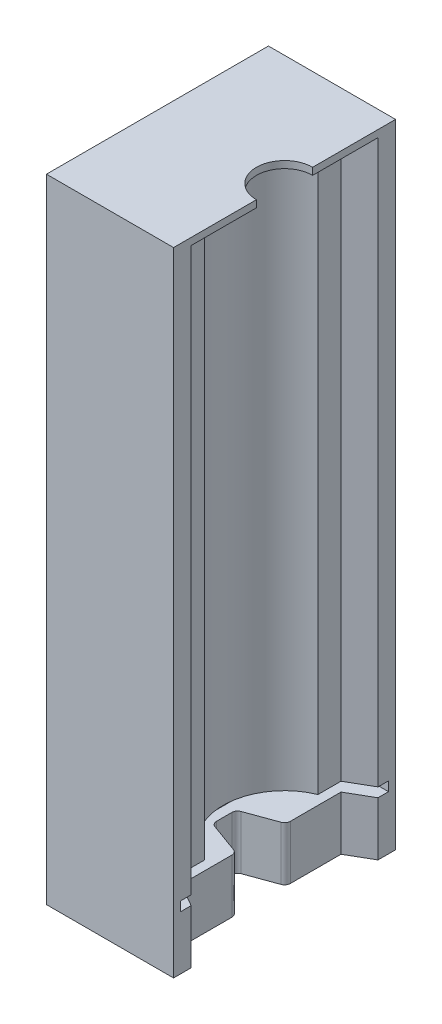
SolidWorks part; units mm, degrees
ref_plane "Спереди" through (0, 0, 0) normal (0, 0, 1) x (1, 0, 0)
ref_plane "Сверху" through (0, 0, 0) normal (0, 1, 0) x (1, 0, 0)
ref_plane "Справа" through (0, 0, 0) normal (1, 0, 0) x (0, 0, -1)
sketch "Эскиз1" plane through (0, 0, 0) normal (0, 1, 0) x (1, 0, 0)
  line L0 (0, -15.95) -> (0, -18.95)
  line L1 (12, -17.75) -> (-12, -17.75) construction
  line L2 (12, -17.75) -> (12, 17.75) construction
  line L3 (12, 17.75) -> (-12, 17.75) construction
  line L4 (-12, -17.75) -> (-12, 17.75) construction
  line L5 (12, -17.75) -> (-12, 17.75) construction
  line L6 (12, 17.75) -> (-12, -17.75) construction
  line L7 (0, 18.95) -> (-21.7, 18.95)
  line L8 (0, 18.95) -> (0, 15.95)
  line L9 (0, -18.95) -> (-21.7, -18.95)
  line L10 (-21.7, 18.95) -> (-21.7, -18.95)
  line L11 (-4, 9.7082) -> (-4, 13.6406)
  line L12 (-4, 13.6406) -> (0, 15.95)
  line L13 (0, 0) -> (-43.4608, 0) construction
  line L14 (0, -18.95) -> (0, -15.95)
  line L15 (-4, -13.6406) -> (0, -15.95)
  line L16 (-4, -9.7082) -> (-4, -13.6406)
  line L17 (-11.7, 17.75) -> (-11.7, -17.75)
  line L18 (-21.7, 17.75) -> (-11.7, 17.75)
  line L19 (-21.7, -17.75) -> (-11.7, -17.75)
  circle A0 centre (0, 0) radius 10.5 construction
  arc A1 (-4, 9.7082) -> (-4, -9.7082) centre (0, 0) ccw
  point P12 (-10.5, 0)
  point P15 (-4, 11.6744)
  dimension "D1" = 21
  dimension "D6" = 4
  dimension "D2" = 35.5
  dimension "D3" = 24
  dimension "D4" = 1.2
  dimension "D5" = 1.2
  dimension "D7" = 3.9324
  dimension "D8" = 3
  dimension "D9" = 120
  dimension "D10" = 10
extrude "Бобышка-Вытянуть1" add sketch "Эскиз1" along normal blind 96 contours A1 L11 L12 L8 L7 L10 L18 L17 L19 L9 L0 L15 L16
sketch "Эскиз2" plane through (0, 96, 0) normal (0, 1, 0) x (1, 0, 0)
  line L0 (0, -4.8) -> (0, -18.95)
  line L1 (-21.7, 18.95) -> (0, 18.95)
  line L2 (-21.7, 18.95) -> (-21.7, -18.95)
  line L3 (-21.7, -18.95) -> (0, -18.95)
  line L4 (0, 18.95) -> (0, 4.8)
  arc A0 (0, 4.8) -> (0, -4.8) centre (0, 0) ccw
  dimension "D1" = 9.6
  dimension "D2" = 18.95
extrude "Бобышка-Вытянуть2" add sketch "Эскиз2" along normal blind 1.2
sketch "Эскиз3" plane through (0, 0, 0) normal (0, -1, 0) x (1, 0, 0)
  line L0 (0, -18.95) -> (0, -17.75)
  line L1 (12, -17.75) -> (-12, -17.75) construction
  line L2 (12, -17.75) -> (12, 17.75) construction
  line L3 (12, 17.75) -> (-12, 17.75) construction
  line L4 (-12, -17.75) -> (-12, 17.75) construction
  line L5 (12, -17.75) -> (-12, 17.75) construction
  line L6 (12, 17.75) -> (-12, -17.75) construction
  line L7 (0, -17.75) -> (-7, -17.75)
  line L8 (-7, -17.75) -> (-12, -9.0897)
  line L9 (-12, -9.0897) -> (-12, 9.0897)
  line L10 (-12, 9.0897) -> (-7, 17.75)
  line L11 (-7, 17.75) -> (0, 17.75)
  line L12 (0, 17.75) -> (0, 18.95)
  line L13 (0, 18.95) -> (-21.7, 18.95)
  line L14 (-21.7, 18.95) -> (-21.7, -18.95)
  line L15 (-21.7, -18.95) -> (0, -18.95)
  line L16 (-11.7, -17.75) -> (-11.7, 17.75) construction
  circle A0 centre (-17.7, 2.45) radius 1.6
  circle A1 centre (-17.7, -2.05) radius 0.6
  circle A2 centre (-17.7, 6.95) radius 0.6
  point P0 (0, 0)
  point P26 (0, 0)
  point P29 (0, 0)
  dimension "D7" = 3.2
  dimension "D8" = 1.2
  dimension "D9" = 1.2
  dimension "D1" = 7
  dimension "D2" = 30
  dimension "D3" = 30
  dimension "D4" = 7
  dimension "D5" = 18.1795
  dimension "D6" = 1.2
  dimension "D10" = 4.5
  dimension "D11" = 4.5
  dimension "D12" = 6
  dimension "D13" = 21.4
extrude "Бобышка-Вытянуть3" add sketch "Эскиз3" along normal blind 1.6
sketch "Эскиз4" plane through (0, -1.6, 0) normal (0, -1, 0) x (1, 0, 0)
  line L0 (0, -17.75) -> (0, -18.95)
  line L1 (0, -18.95) -> (-21.7, -18.95)
  line L2 (-21.7, -18.95) -> (-21.7, 18.95)
  line L3 (-21.7, 18.95) -> (0, 18.95)
  line L4 (0, 18.95) -> (0, 17.75)
  line L5 (-4, 9.7082) -> (-4, 4.2958)
  line L6 (-4, 4.2958) -> (-10.3078, 2)
  line L7 (-10.3078, 2) -> (-10.3078, -2)
  line L8 (-4, -9.7082) -> (-4, -4.2958)
  line L9 (-4, -4.2958) -> (-10.3078, -2)
  line L11 (0, 17.75) -> (-7, 17.75)
  line L12 (-7, 17.75) -> (-11.7, 9.6094)
  line L13 (-11.7, 9.6094) -> (-11.7, -9.6094)
  line L14 (-11.7, -9.6094) -> (-7, -17.75)
  line L15 (-7, -17.75) -> (0, -17.75)
  line L16 (0, -17.75) -> (0, -15.95)
  line L17 (0, -15.95) -> (-4, -13.6406)
  line L18 (-4, -13.6406) -> (-4, -9.7082)
  line L19 (-4, 9.7082) -> (-4, 13.6406)
  line L20 (-4, 13.6406) -> (0, 15.95)
  line L21 (0, 15.95) -> (0, 17.75)
  line L27 (0, -17.75) -> (0, -15.95)
  line L28 (0, -15.95) -> (-4, -13.6406)
  line L29 (-4, -13.6406) -> (-4, -9.7082)
  line L30 (-4, 9.7082) -> (-4, 13.6406)
  line L31 (-4, 13.6406) -> (0, 15.95)
  line L32 (0, 15.95) -> (0, 17.75)
  circle A0 centre (-17.7, 6.95) radius 0.6 construction
  arc A1 (-4, 9.7082) -> (-4, -9.7082) centre (0, 0) ccw
  circle A3 centre (-17.7, 2.45) radius 1.6 construction
  circle A4 centre (-17.7, -2.05) radius 0.6 construction
  circle A5 centre (-17.7, 6.95) radius 0.6
  circle A6 centre (-17.7, 2.45) radius 1.6
  circle A7 centre (-17.7, -2.05) radius 0.6
  circle A8 centre (-13.2, 10.45) radius 7.5 construction
  circle A9 centre (-17.7, 2.6558) radius 1.5 construction
  dimension "D2" = 15
  dimension "D3" = 8.5
  dimension "D4" = 8.5
  dimension "D5" = 110
  dimension "D6" = 110
  dimension "D7" = 9
  dimension "D8" = 4
  dimension "D1" = 0
extrude "Бобышка-Вытянуть4" add sketch "Эскиз4" along normal blind 1.2
fillet "Скругление1" radius 1 4 edges at (-10.3078, -2.2, -2) (-10.3078, -2.2, 2) (-4, -2.2, 4.2958) (-4, -2.2, -4.2958)
sketch "Эскиз5" plane through (0, -2.8, 0) normal (0, -1, 0) x (1, 0, 0)
  line L0 (-21.7, 18.95) -> (-21.7, -18.95) construction
  line L1 (0, 18.95) -> (-21.7, 18.95) construction
  circle A0 centre (-13.2, 10.25) radius 1.5
  dimension "D1" = 3
  dimension "D2" = 8.5
  dimension "D3" = 8.7
extrude "Вырез-Вытянуть1" cut sketch "Эскиз5" against normal blind 2
sketch "Эскиз6" plane through (0, -2.8, 0) normal (0, -1, 0) x (1, 0, 0)
  line L0 (-10.3078, 0) -> (-30.784, 0) construction
  line L1 (-10.3078, -1.2998) -> (-10.3078, 1.2998) construction
  circle A0 centre (-13.2, 10.25) radius 1.5 construction
  circle A1 centre (-13.2, 10.25) radius 1.5 construction
  circle A2 centre (-13.2, -10.25) radius 1.5
extrude "Вырез-Вытянуть2" cut sketch "Эскиз6" against normal blind 2
sketch "Эскиз9" plane through (0, -2.8, 0) normal (0, -1, 0) x (1, 0, 0)
  line L0 (-1.2, 16.6428) -> (-1.2, 17.75)
  line L1 (-1.2, 17.75) -> (-20.5, 17.75)
  line L2 (-20.5, 17.75) -> (-20.5, -17.75)
  line L3 (-20.5, -17.75) -> (-1.2, -17.75)
  line L4 (-1.2, -17.75) -> (-1.2, -16.6428)
  line L5 (-1.2, -16.6428) -> (-5.2, -14.3334)
  line L6 (-5.2, -14.3334) -> (-5.2, -5.1361)
  line L7 (-5.2, -5.1361) -> (-10.0602, -3.3671)
  line L8 (-11.5078, -1.2998) -> (-11.5078, 1.2998)
  line L9 (-10.0602, 3.3671) -> (-5.2, 5.1361)
  line L10 (-5.2, 5.1361) -> (-5.2, 14.3334)
  line L11 (-5.2, 14.3334) -> (-1.2, 16.6428)
  line L12 (-9.6498, 2.2395) -> (-4.658, 4.0564)
  line L13 (-4, 4.996) -> (-4, 13.6406)
  line L14 (-4, 13.6406) -> (0, 15.95)
  line L15 (0, 15.95) -> (0, 18.95)
  line L16 (0, 18.95) -> (-21.7, 18.95)
  line L17 (-21.7, 18.95) -> (-21.7, -18.95)
  line L18 (-21.7, -18.95) -> (0, -18.95)
  line L19 (0, -18.95) -> (0, -15.95)
  line L20 (0, -15.95) -> (-4, -13.6406)
  line L21 (-4, -13.6406) -> (-4, -4.996)
  line L22 (-4.658, -4.0564) -> (-9.6498, -2.2395)
  line L23 (-10.3078, -1.2998) -> (-10.3078, 1.2998)
  line L24 (-9.6498, 2.2395) -> (-4.658, 4.0564)
  line L25 (-4, 4.996) -> (-4, 13.6406)
  line L26 (-4, 13.6406) -> (0, 15.95)
  line L27 (0, 15.95) -> (0, 18.95)
  line L28 (0, 18.95) -> (-21.7, 18.95)
  line L29 (-21.7, 18.95) -> (-21.7, -18.95)
  line L30 (-21.7, -18.95) -> (0, -18.95)
  line L31 (0, -18.95) -> (0, -15.95)
  line L32 (0, -15.95) -> (-4, -13.6406)
  line L33 (-4, -13.6406) -> (-4, -4.996)
  line L34 (-4.658, -4.0564) -> (-9.6498, -2.2395)
  line L35 (-10.3078, -1.2998) -> (-10.3078, 1.2998)
  arc A0 (-5.2, -5.1361) -> (-5.2, -5.1361) centre (-5.2, -5.1361) ccw
  arc A1 (-11.5078, -1.2998) -> (-10.0602, -3.3671) centre (-9.3078, -1.2998) ccw
  arc A2 (-10.0602, 3.3671) -> (-11.5078, 1.2998) centre (-9.3078, 1.2998) ccw
  arc A3 (-5.2, 5.1361) -> (-5.2, 5.1361) centre (-5.2, 5.1361) ccw
  arc A4 (-4.658, 4.0564) -> (-4, 4.996) centre (-5, 4.996) ccw
  arc A5 (-4, -4.996) -> (-4.658, -4.0564) centre (-5, -4.996) ccw
  arc A6 (-10.3078, -1.2998) -> (-9.6498, -2.2395) centre (-9.3078, -1.2998) ccw
  arc A7 (-9.6498, 2.2395) -> (-10.3078, 1.2998) centre (-9.3078, 1.2998) ccw
  arc A8 (-4.658, 4.0564) -> (-4, 4.996) centre (-5, 4.996) ccw
  arc A9 (-4, -4.996) -> (-4.658, -4.0564) centre (-5, -4.996) ccw
  arc A10 (-10.3078, -1.2998) -> (-9.6498, -2.2395) centre (-9.3078, -1.2998) ccw
  arc A11 (-9.6498, 2.2395) -> (-10.3078, 1.2998) centre (-9.3078, 1.2998) ccw
  dimension "D1" = 0
  dimension "D2" = 1.2
extrude "Бобышка-Вытянуть6" add sketch "Эскиз9" along normal blind 8
sketch "Эскиз10" plane through (0, -10.8, 0) normal (0, -1, 0) x (1, 0, 0)
  line L0 (-1.2, 17.75) -> (-1.2, 16.6428)
  line L1 (-1.2, 16.6428) -> (-5.2, 14.3334)
  line L2 (-5.2, 14.3334) -> (-5.2, 17.75)
  line L3 (-1.2, 17.75) -> (-20.5, 17.75) construction
  line L4 (-5.2, 17.75) -> (-1.2, 17.75)
  line L5 (-16.5, 17.75) -> (-20.5, 13.75)
  line L6 (-20.5, 17.75) -> (-20.5, -17.75) construction
  line L7 (-20.5, 13.75) -> (-20.5, 17.75)
  line L8 (-20.5, 17.75) -> (-16.5, 17.75)
  line L9 (-10.3078, 0) -> (-20.5, 0) construction
  line L10 (-10.3078, -1.2998) -> (-10.3078, 1.2998) construction
  line L11 (-20.5, -13.75) -> (-20.5, -17.75)
  line L12 (-16.5, -17.75) -> (-20.5, -13.75)
  line L13 (-20.5, -17.75) -> (-16.5, -17.75)
  line L14 (-5.2, -14.3334) -> (-5.2, -17.75)
  line L15 (-1.2, -16.6428) -> (-5.2, -14.3334)
  line L16 (-1.2, -17.75) -> (-1.2, -16.6428)
  line L17 (-5.2, -17.75) -> (-1.2, -17.75)
  circle A0 centre (-3.6, 16.55) radius 0.6
  circle A1 centre (-19.3, 16.55) radius 0.6
  circle A2 centre (-19.3, -16.55) radius 0.6
  circle A3 centre (-3.6, -16.55) radius 0.6
  dimension "D1" = 1.2
  dimension "D6" = 1.2
  dimension "D2" = 1.2
  dimension "D3" = 1.6
  dimension "D4" = 4
  dimension "D5" = 4
  dimension "D7" = 1.2
  dimension "D8" = 1.2
extrude "Бобышка-Вытянуть7" add sketch "Эскиз10" against normal blind 4
